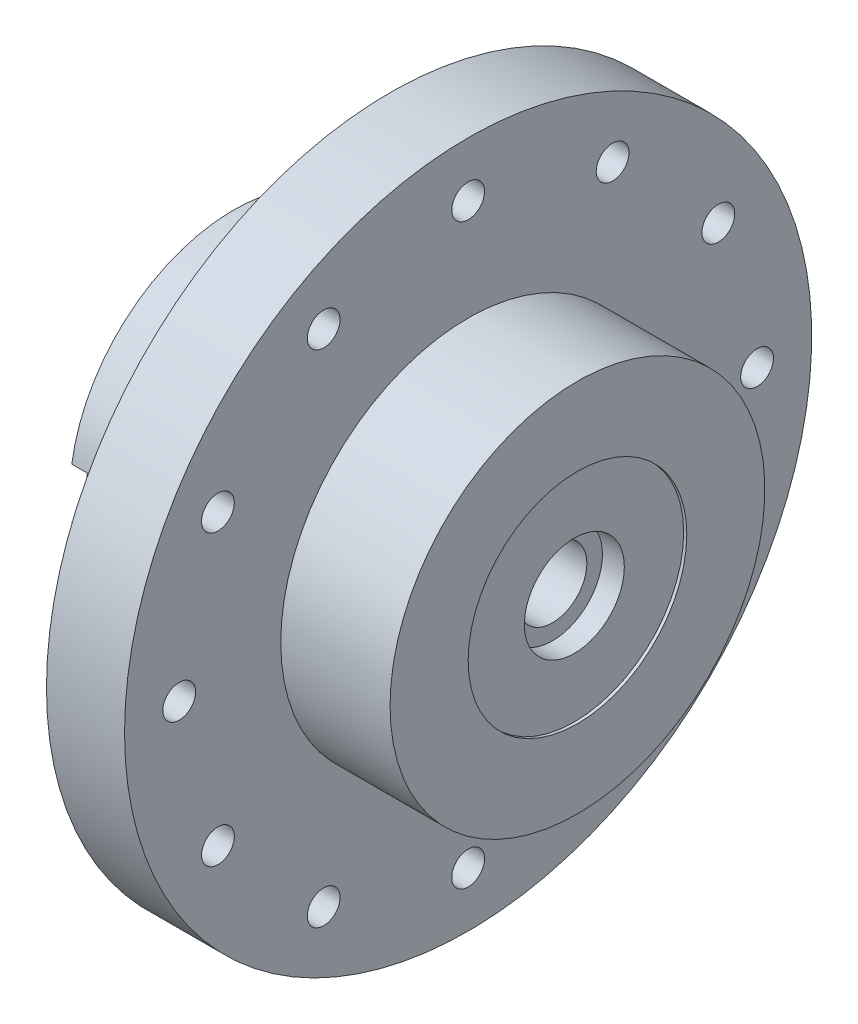
SolidWorks part; units mm, degrees
ref_plane "Front Plane" through (0, 0, 0) normal (0, 0, 1) x (1, 0, 0)
ref_plane "Top Plane" through (0, 0, 0) normal (0, 1, 0) x (1, 0, 0)
ref_plane "Right Plane" through (0, 0, 0) normal (1, 0, 0) x (0, 0, -1)
sketch "Sketch1" plane through (0, 0, 0) normal (0, 0, 1) x (1, 0, 0)
  line L0 (-290.1351, 60) -> (-325.1351, 60)
  line L1 (-325.1351, 60) -> (-325.1351, 110)
  line L2 (-325.1351, 110) -> (-350.1351, 110)
  line L3 (-350.1351, 110) -> (-350.1351, 80)
  line L4 (-350.1351, 80) -> (-369.1351, 80)
  line L5 (-369.1351, 80) -> (-369.1351, 52.5)
  line L6 (-369.1351, 52.5) -> (-400.1351, 52.5)
  line L7 (-400.1351, 52.5) -> (-400.1351, 0)
  line L8 (-400.1351, 0) -> (-290.1351, 0)
  line L9 (-290.1351, 0) -> (-290.1351, 60)
  dimension "D1" = 52.5
  dimension "D2" = 80
  dimension "D3" = 110
  dimension "D4" = 60
  dimension "D5" = 25
  dimension "D6" = 35
  dimension "D7" = 19
  dimension "D8" = 50
revolve "Revolve1" add sketch "Sketch1" angle 360 about L8
ref_axis "Axis1" through (-290.1351, 0, 0) along (-1, 0, 0)
sketch "Sketch2" plane through (-290.1351, 0, 0) normal (1, 0, 0) x (0, 0, -1)
  circle A2 centre (0, 0) radius 35
  circle A3 centre (0, 0) radius 35
  dimension "D1" = 25
extrude "Cut-Extrude1" cut sketch "Sketch2" against normal blind 1
sketch "Sketch3" plane through (-325.1351, 0, 0) normal (1, 0, 0) x (0, 0, -1)
  circle A0 centre (0, 0) radius 92.5 construction
  circle A1 centre (0, 92.5) radius 5.25
  dimension "D1" = 10.5
  dimension "D2" = 185
extrude "Cut-Extrude2" cut sketch "Sketch3" against normal up to next
pattern_circular "CirPattern1" count 12 over 360 about axis through (0, 0, 0) along (1, 0, 0) of "Cut-Extrude2"
sketch "Sketch4" plane through (0, 0, 0) normal (0, 0, 1) x (1, 0, 0)
  line L0 (-291.1351, 16) -> (-298.1351, 16)
  line L1 (-298.1351, 16) -> (-298.1351, 11)
  line L2 (-298.1351, 11) -> (-328.6351, 11)
  line L3 (-374.1351, 11) -> (-374.1351, 16)
  line L4 (-374.1351, 16) -> (-381.1351, 16)
  line L5 (-381.1351, 16) -> (-381.1351, 0)
  line L6 (-290.1351, 0) -> (-290.1351, 60) construction
  line L7 (-290.1351, -60) -> (-290.1351, 60) construction
  line L8 (-291.1351, 16) -> (-291.1351, 0)
  line L9 (-290.1351, 0) -> (-325.1351, 0) construction
  line L10 (-353.6351, 17) -> (-353.6351, 11)
  line L11 (-353.6351, 17) -> (-328.6351, 17)
  line L12 (-328.6351, 17) -> (-328.6351, 11)
  line L13 (-353.6351, 11) -> (-374.1351, 11)
  line L14 (-291.1351, 0) -> (-381.1351, 0)
  dimension "D1" = 1
  dimension "D2" = 7
  dimension "D3" = 16
  dimension "D4" = 11
  dimension "D5" = 90
  dimension "D6" = 25
  dimension "D7" = 27.5
  dimension "D8" = 17
revolve "Cut-Revolve1" cut sketch "Sketch4" angle 360 about L14
ref_plane "Plane1" through (0, 0, 38) normal (0, 0, 1) x (1, 0, 0)
sketch "Sketch8" plane through (0, 0, 38) normal (0, 0, 1) x (1, 0, 0)
  line L0 (-400.1351, 0) -> (-313.1351, 0)
  line L1 (-400.1351, 52.5) -> (-400.1351, -52.5) construction
  line L2 (-290.1351, 0) -> (-325.1351, 0) construction
  line L3 (-400.1351, 0) -> (-400.1351, 16)
  line L4 (-400.1351, 16) -> (-395.1351, 16)
  line L5 (-395.1351, 16) -> (-395.1351, 11)
  line L11 (-332.6351, 11) -> (-320.1351, 11)
  line L12 (-320.1351, 11) -> (-320.1351, 16)
  line L13 (-320.1351, 16) -> (-313.1351, 16)
  line L14 (-313.1351, 16) -> (-313.1351, 0)
  line L15 (-290.1351, -35) -> (-290.1351, 35) construction
  line L16 (-332.6351, 11) -> (-332.6351, 30)
  line L17 (-332.6351, 30) -> (-352.6351, 30)
  line L18 (-352.6351, 30) -> (-352.6351, 11)
  line L19 (-352.6351, 11) -> (-395.1351, 11)
  dimension "D1" = 7
  dimension "D2" = 16
  dimension "D3" = 12.5
  dimension "D4" = 20
  dimension "D5" = 11
  dimension "D6" = 23
  dimension "D7" = 30
  dimension "D8" = 5
revolve "Cut-Revolve2" cut sketch "Sketch8" angle 360 about L0
sketch "Sketch9" plane through (-400.1351, 0, 0) normal (-1, 0, 0) x (0, 0, 1)
  circle A0 centre (0, 30) radius 5
  dimension "D1" = 10
  dimension "D2" = 30
extrude "Cut-Extrude3" cut sketch "Sketch9" against normal blind 10
pattern_circular "CirPattern2" count 4 over 180 about axis through (0, 0, 0) along (1, 0, 0) of "Cut-Extrude3"
